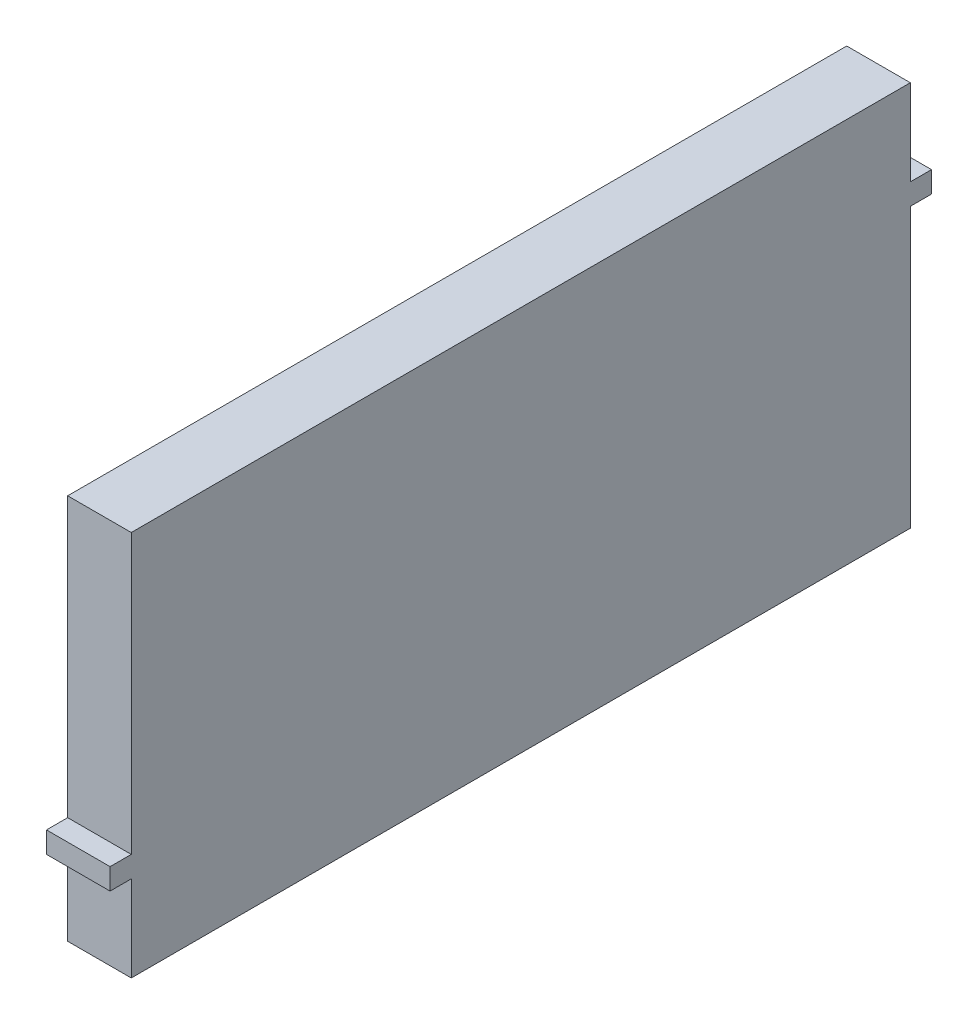
SolidWorks part; units mm, degrees
material "Balsa"
ref_plane "Front Plane" through (0, 0, 0) normal (0, 0, 1) x (1, 0, 0)
ref_plane "Top Plane" through (0, 0, 0) normal (0, 1, 0) x (1, 0, 0)
ref_plane "Right Plane" through (0, 0, 0) normal (1, 0, 0) x (0, 0, -1)
sketch "Sketch1" plane through (243.0177, 0, 0) normal (1, 0, 0) x (0, 0, -1)
  line L12 (-319.6812, 406.6592) -> (-322.8562, 406.6592)
  line L13 (-322.8562, 406.6592) -> (-322.8562, 416.216)
  line L14 (-322.8562, 416.216) -> (-439.5374, 416.216)
  line L15 (-439.5374, 416.216) -> (-439.5374, 377.7667)
  line L16 (-439.5374, 377.7667) -> (-442.7124, 377.7667)
  line L17 (-442.7124, 377.7667) -> (-442.7124, 374.5917)
  line L18 (-442.7124, 374.5917) -> (-439.5374, 374.5917)
  line L19 (-439.5374, 374.5917) -> (-439.5374, 358.431)
  line L20 (-439.5374, 358.431) -> (-322.8562, 358.431)
  line L21 (-322.8562, 358.431) -> (-322.8562, 403.4842)
  line L22 (-322.8562, 403.4842) -> (-319.6812, 403.4842)
  line L23 (-319.6812, 403.4842) -> (-319.6812, 406.6592)
  line L24 (-319.6812, 406.6592) -> (-322.8562, 406.6592)
  line L25 (-322.8562, 406.6592) -> (-322.8562, 419.518)
  line L27 (-439.5374, 419.518) -> (-439.5374, 377.7667)
  line L28 (-439.5374, 377.7667) -> (-442.7124, 377.7667)
  line L29 (-442.7124, 377.7667) -> (-442.7124, 374.5917)
  line L30 (-442.7124, 374.5917) -> (-439.5374, 374.5917)
  line L31 (-439.5374, 374.5917) -> (-439.5374, 361.733)
  line L33 (-322.8562, 361.733) -> (-322.8562, 403.4842)
  line L34 (-322.8562, 403.4842) -> (-319.6812, 403.4842)
  line L35 (-319.6812, 403.4842) -> (-319.6812, 406.6592)
  line L192 (-442.7124, 419.518) -> (-439.5374, 419.518) construction
  line L193 (-442.7124, 419.518) -> (-439.5374, 419.518) construction
  line L206 (-322.8562, 419.518) -> (-319.6812, 419.518) construction
  line L207 (-322.8562, 419.518) -> (-319.6812, 419.518) construction
  line L208 (-442.7124, 361.733) -> (-439.5374, 361.733) construction
  line L209 (-442.7124, 361.733) -> (-439.5374, 361.733) construction
  line L210 (-322.8562, 361.733) -> (-319.6812, 361.733) construction
  line L211 (-322.8562, 361.733) -> (-319.6812, 361.733) construction
  line L212 (-439.5374, 361.733) -> (-322.8562, 361.733)
  line L213 (-439.5374, 419.518) -> (-322.8562, 419.518)
  dimension "D1" = 0
extrude "Boss-Extrude1" add sketch "Sketch1" along normal up to surface (9.525 mm away)
